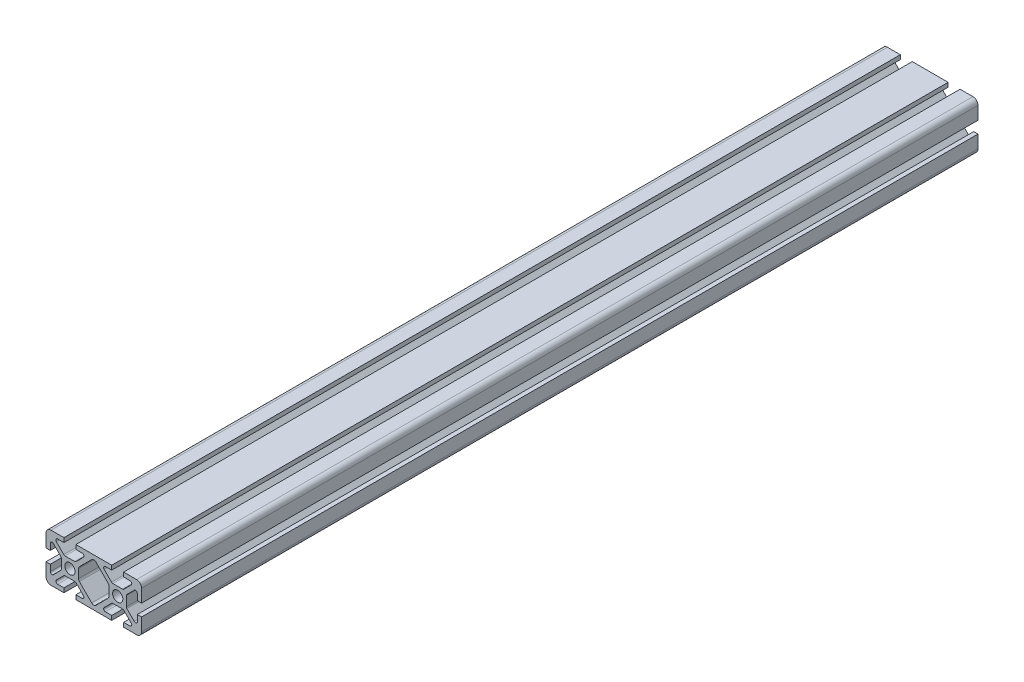
SolidWorks part; units mm, degrees
material "6063-T6"
ref_plane "Front Plane" through (0, 0, 0) normal (0, 0, 1) x (1, 0, 0)
ref_plane "Top Plane" through (0, 0, 0) normal (0, 1, 0) x (1, 0, 0)
ref_plane "Right Plane" through (0, 0, 0) normal (1, 0, 0) x (0, 0, -1)
sketch "Sketch1" plane through (0, 0, 0) normal (0, 0, 1) x (1, 0, 0)
  line L0 (10, 10) -> (10, -10) construction
  line L1 (-20, 0) -> (20, 0) construction
  line L2 (12.5, -10) -> (20, -10)
  line L3 (20, -10) -> (20, -2.5)
  line L4 (12.5, -10) -> (12.5, -8.2134)
  line L5 (12.5, -8.2134) -> (16.95, -8.2134)
  line L6 (16.95, -8.2134) -> (12.3366, -3.6)
  line L7 (10, 0) -> (20, -10) construction
  line L8 (20, -2.5) -> (18.2134, -2.5)
  line L9 (18.2134, -2.5) -> (18.2134, -6.95)
  line L10 (18.2134, -6.95) -> (13.6, -2.3366)
  line L11 (15.9067, -4.6433) -> (14.6433, -5.9067) construction
  line L12 (0, 10) -> (0, -10) construction
  line L13 (0, -10) -> (-20, -10) construction
  line L14 (-10, 10) -> (10, 10) construction
  line L15 (20, 2.5) -> (20, -2.5) construction
  circle A0 centre (10, 0) radius 2.15
  arc A1 (15.5015, -8.2134) -> (15.9257, -7.1891) centre (15.5015, -7.6134) ccw construction
  point P8 (10, -3.6)
  point P16 (15.275, -5.275)
  point P30 (20, 0)
  dimension "Center Hole Diameter" = 4.3
  dimension "D3" = 0.6
  dimension "Rail Width" = 20
  dimension "T-Slot Width" = 5
  dimension "Slot Depth" = 6.4
  dimension "Rail Height" = 40
  dimension "Inner Slot Width" = 13.9
  dimension "Hole Spacing" = 20
sketch "Sketch2" plane through (0, 0, 0) normal (1, 0, 0) x (0, 0, -1)
  line L0 (-175, -10) -> (175, -10) construction
  line L1 (-135, 0) -> (135, 0) construction
  point P6 (-135, 0)
  point P8 (135, 0)
  dimension "Length" = 350
  dimension "D1" = 40
sketch "Sketch3" plane through (0, 0, 0) normal (0, 0, 1) x (1, 0, 0)
  line L0 (12.5, -10) -> (17.9, -10)
  line L1 (12.5, -10) -> (20, -10) construction
  line L2 (12.5, -10) -> (12.5, -8.2134) construction
  line L3 (12.5, -8.2134) -> (16.95, -8.2134) construction
  line L4 (12.5, -8.2134) -> (12.5, -10)
  line L5 (12.5, -8.2134) -> (16.95, -8.2134)
  line L6 (10, -3.6) -> (12.3366, -3.6)
  line L7 (16.95, -8.2134) -> (12.3366, -3.6) construction
  line L8 (12.3366, -3.6) -> (16.95, -8.2134)
  line L9 (20, -10) -> (20, -2.5) construction
  line L10 (18.2134, -6.95) -> (13.6, -2.3366) construction
  line L11 (18.2134, -2.5) -> (18.2134, -6.95) construction
  line L12 (18.2134, -6.95) -> (18.2134, -2.5)
  line L13 (20, -2.5) -> (18.2134, -2.5) construction
  line L14 (18.2134, -2.5) -> (20, -2.5)
  line L15 (20, -2.5) -> (20, -7.9)
  line L16 (18.2134, -6.95) -> (13.6, -2.3366)
  line L17 (13.6, 0) -> (13.6, -2.3366)
  line L18 (-20, 0) -> (20, 0) construction
  line L19 (10, -3.6) -> (10, -2.15)
  line L20 (10, 10) -> (10, -10) construction
  line L21 (13.6, 0) -> (12.15, 0)
  arc A5 (17.9, -10) -> (20, -7.9) centre (17.9, -7.9) ccw
  circle A10 centre (10, 0) radius 2.15 construction
  arc A11 (10, -2.15) -> (12.15, 0) centre (10, 0) ccw
  dimension "D1" = 2.1
extrude "Boss-Extrude1" add sketch "Sketch3" along normal mid plane 350
sketch "Sketch4" plane through (0, 0, 0) normal (0, 0, 1) x (1, 0, 0)
  line L0 (10, -3.6) -> (7.6634, -3.6)
  line L4 (7.6634, -3.6) -> (3.05, -8.2134)
  line L5 (3.05, -8.2134) -> (7.5, -8.2134)
  line L6 (7.5, -8.2134) -> (7.5, -10)
  line L18 (7.5, -10) -> (0, -10)
  line L19 (12.5, -10) -> (12.5, -8.2134) construction
  line L20 (12.5, -8.2134) -> (16.95, -8.2134) construction
  line L21 (10, -3.6) -> (12.3366, -3.6) construction
  line L22 (16.95, -8.2134) -> (12.3366, -3.6) construction
  line L23 (0, -8.7366) -> (6.4, -2.3366)
  line L24 (0, 10) -> (0, -10) construction
  line L25 (6.4, -2.3366) -> (6.4, 0)
  line L26 (-20, 0) -> (20, 0) construction
  line L27 (6.4, 0) -> (7.85, 0)
  line L28 (13.6, 0) -> (12.15, 0) construction
  line L29 (0, -8.7366) -> (0, -10)
  line L30 (10, -2.15) -> (10, -3.6)
  circle A4 centre (10, 0) radius 2.15 construction
  arc A5 (7.85, 0) -> (10, -2.15) centre (10, 0) ccw
extrude "Boss-Extrude2" add sketch "Sketch4" along normal mid plane 350
mirror "Mirror1" about plane through (0, 0, 0) normal (1, 0, 0) of bodies 137 134
mirror "Mirror2" about plane through (0, 0, 0) normal (0, 1, 0) of bodies 135
fillet "Fillet1" radius 0.75 24 edges at (-7.6634, -3.6, 0) (-12.3366, -3.6, 0) (12.3366, -3.6, 0) (7.6634, -3.6, 0) (-3.05, -8.2134, 0) (-18.2134, -6.95, 0) (-16.95, -8.2134, 0) (-13.6, -2.3366, 0) (-18.2134, 6.95, 0) (-16.95, 8.2134, 0) (-12.3366, 3.6, 0) (-7.6634, 3.6, 0) (-13.6, 2.3366, 0) (-3.05, 8.2134, 0) (3.05, 8.2134, 0) (13.6, -2.3366, 0) (18.2134, 6.95, 0) (13.6, 2.3366, 0) (7.6634, 3.6, 0) (12.3366, 3.6, 0) (16.95, 8.2134, 0) (18.2134, -6.95, 0) (16.95, -8.2134, 0) (3.05, -8.2134, 0)
fillet "Fillet2" radius 1.25 6 edges at (0, -8.7366, 0) (-6.4, -2.3366, 0) (-6.4, 2.3366, 0) (6.4, -2.3366, 0) (6.4, 2.3366, 0) (0, 8.7366, 0)
equation "\"D1@Sketch3\" = \"D3@Sketch1\" * 3.5"
equation "\"D1@Boss-Extrude1\" = \"Length@Sketch2\""
equation "\"D1@Boss-Extrude2\" = \"Length@Sketch2\""
equation "\"D1@Sketch2\"=\"Rail Height@Sketch1\""
